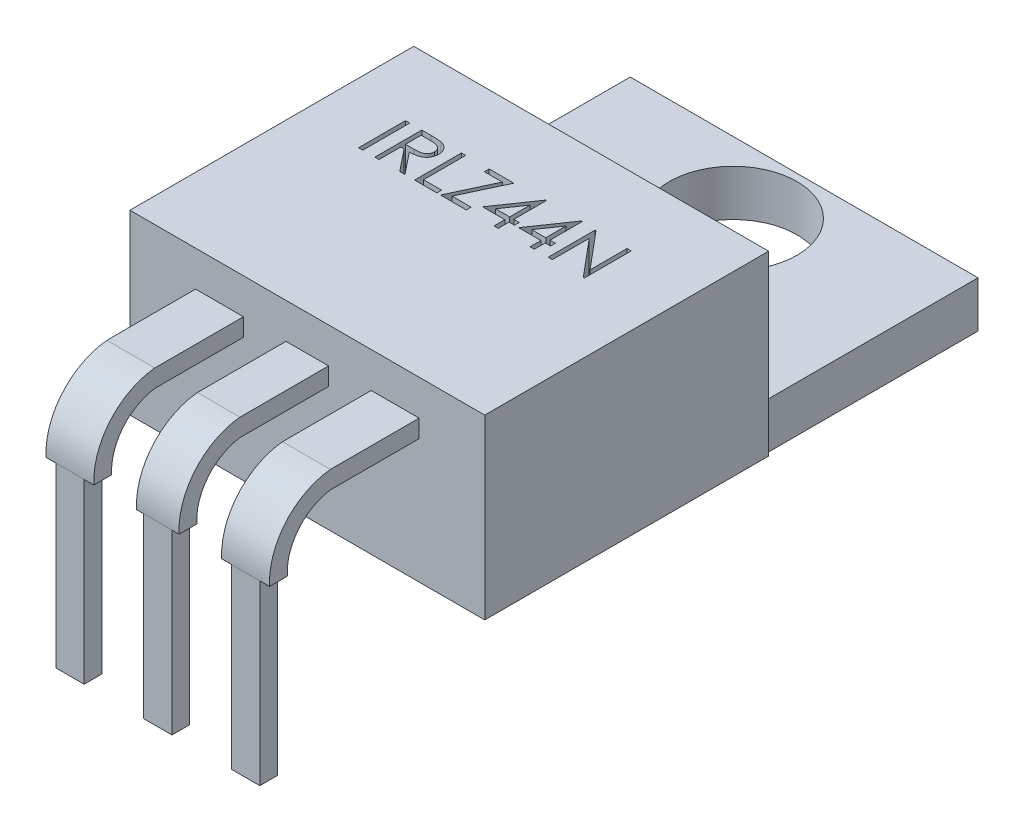
SolidWorks part; units mm, degrees
ref_plane "Ön Düzlem" through (0, 0, 0) normal (0, 0, 1) x (1, 0, 0)
ref_plane "Üst Düzlem" through (0, 0, 0) normal (0, 1, 0) x (1, 0, 0)
ref_plane "Sağ Düzlem" through (0, 0, 0) normal (1, 0, 0) x (0, 0, -1)
sketch "Sketch1" plane through (0, 0, 0) normal (0, 1, 0) x (1, 0, 0)
  line L1 (-5, 4) -> (5, 4)
  line L2 (-5, 4) -> (-5, -4)
  line L3 (-5, -4) -> (5, -4)
  line L4 (5, 4) -> (5, -4)
  line L5 (-5, 4) -> (5, -4) construction
  line L6 (-5, -4) -> (5, 4) construction
  point P0 (0, 0)
  dimension "D1" = 10
  dimension "D2" = 8
extrude "Boss-Extrude1" add sketch "Sketch1" along normal blind 5
sketch "Sketch2" plane through (0, 0, -4) normal (0, 0, -1) x (-1, 0, 0)
  line L1 (-4.9, 0) -> (4.9, 0)
  line L2 (-4.9, 0) -> (-4.9, 1.3)
  line L3 (-4.9, 1.3) -> (4.9, 1.3)
  line L4 (4.9, 0) -> (4.9, 1.3)
  line L5 (-5, 5) -> (-5, 0) construction
  line L6 (5, 5) -> (5, 0) construction
  dimension "D1" = 1.3
  dimension "D2" = 0.1
  dimension "D3" = 0.1
extrude "Boss-Extrude2" add sketch "Sketch2" along normal blind 6
sketch "Sketch3" plane through (0, 0, 4) normal (0, 0, 1) x (1, 0, 0)
  line L0 (5, 5) -> (5, 0) construction
  line L1 (-3.15, 4) -> (3.15, 4)
  line L2 (-3.15, 4) -> (-3.15, 3.5)
  line L3 (-3.15, 3.5) -> (3.15, 3.5)
  line L4 (3.15, 4) -> (3.15, 3.5)
  line L5 (-3.15, 4) -> (3.15, 3.5) construction
  line L6 (-3.15, 3.5) -> (3.15, 4) construction
  line L8 (-5, 5) -> (-5, 0) construction
  line L9 (-5, 0) -> (5, 0) construction
  point P0 (0, 3.75)
  dimension "D1" = 0.5
  dimension "D2" = 1.85
  dimension "D3" = 1.85
  dimension "D4" = 4
extrude "Boss-Extrude3" add sketch "Sketch3" along normal blind 2.5
sketch "Sketch4" plane through (-3.15, 0, 0) normal (-1, 0, 0) x (0, 0, 1)
  line L2 (7.7145, 2) -> (7.7145, -3)
  line L3 (7.7145, -3) -> (8.2145, -3)
  line L4 (8.2145, 2) -> (8.2145, -3)
  line L11 (4, 4) -> (4, 3.5)
  line L12 (4, 3.5) -> (6.5, 3.5)
  line L13 (6.5, 3.5) -> (6.5, 4)
  line L14 (6.5, 4) -> (4, 4)
  line L17 (6.5, 3.5) -> (6.5, 4)
  arc A0 (6.5, 3.5) -> (7.7145, 2) centre (6.2931, 2.0908) cw
  arc A1 (6.5, 4) -> (8.2145, 2) centre (6.3035, 2.0967) cw
  dimension "D1" = 0.5
  dimension "D2" = 0
  dimension "D3" = 5
extrude "Boss-Extrude4" add sketch "Sketch4" against normal up to vertex
sketch "Sketch5" plane through (0, 4, 0) normal (0, 1, 0) x (1, 0, 0)
  line L0 (3.15, -4) -> (-3.15, -4) construction
  line L1 (-1.8, -4) -> (-0.6, -4)
  line L2 (-1.8, -4) -> (-1.8, -9)
  line L3 (-1.8, -9) -> (-0.6, -9)
  line L4 (-0.6, -4) -> (-0.6, -9)
  line L6 (0.6, -4) -> (1.8, -4)
  line L7 (0.6, -4) -> (0.6, -9)
  line L8 (0.6, -9) -> (1.8, -9)
  line L9 (1.8, -4) -> (1.8, -9)
  line L13 (-3.15, -6.5) -> (-3.15, -4) construction
  dimension "D1" = 1.2
  dimension "D2" = 1.2
  dimension "D3" = 1.2
  dimension "D4" = 1.35
  dimension "D5" = 5
  dimension "D6" = 5
extrude "Cut-Extrude1" cut sketch "Sketch5" against normal through all
sketch "Sketch6" plane through (0, 0, 8.2145) normal (0, 0, 1) x (1, 0, 0)
  line L0 (-1.8, -3) -> (-3.15, -3) construction
  line L1 (-3.15, 2) -> (-2.875, 2)
  line L2 (-3.15, 2) -> (-3.15, -3)
  line L3 (-3.15, -3) -> (-2.875, -3)
  line L4 (-2.875, 2) -> (-2.875, -3)
  line L5 (0.6, -3) -> (-0.6, -3) construction
  line L6 (-1.8, 2) -> (-2.075, 2)
  line L7 (-1.8, 2) -> (-1.8, -3)
  line L8 (-1.8, -3) -> (-2.075, -3)
  line L9 (-2.075, 2) -> (-2.075, -3)
  line L10 (-0.6, 2) -> (-0.4, 2)
  line L11 (-0.6, 2) -> (-0.6, -3)
  line L12 (-0.6, -3) -> (-0.4, -3)
  line L13 (-0.4, 2) -> (-0.4, -3)
  line L14 (3.15, -3) -> (1.8, -3) construction
  line L15 (0.6, 2) -> (0.4, 2)
  line L16 (0.6, 2) -> (0.6, -3)
  line L17 (0.6, -3) -> (0.4, -3)
  line L18 (0.4, 2) -> (0.4, -3)
  line L19 (1.8, 2) -> (2.075, 2)
  line L20 (1.8, 2) -> (1.8, -3)
  line L21 (1.8, -3) -> (2.075, -3)
  line L22 (2.075, 2) -> (2.075, -3)
  line L24 (3.15, 2) -> (2.875, 2)
  line L25 (3.15, 2) -> (3.15, -3)
  line L26 (3.15, -3) -> (2.875, -3)
  line L27 (2.875, 2) -> (2.875, -3)
  dimension "D1" = 0.8
  dimension "D2" = 0.275
  dimension "D3" = 0.2
  dimension "D4" = 0.8
  dimension "D5" = 0.275
  dimension "D6" = 0.275
extrude "Cut-Extrude2" cut sketch "Sketch6" against normal blind 3.5
sketch "Sketch7" plane through (0, 1.3, 0) normal (0, 1, 0) x (1, 0, 0)
  line L0 (-4.9, 10) -> (4.9, 10) construction
  circle A0 centre (0, 8) radius 1.8
  point P2 (0, 7.4224)
  dimension "D1" = 3.6
  dimension "D2" = 2
extrude "Cut-Extrude3" cut sketch "Sketch7" against normal blind 3.5
sketch "Sketch8" plane through (0, 5, 0) normal (0, 1, 0) x (1, 0, 0)
  text T0 "IRLZ44N" font "Century Gothic" height in points 5
  point P1 (-3.9243, -0.9913)
  point P2 (-4.6623, -0.9913)
  point P3 (0, 0)
  point P4 (0, 0)
  point P5 (0, 0)
extrude "Cut-Extrude4" cut sketch "Sketch8" against normal blind 3.5
